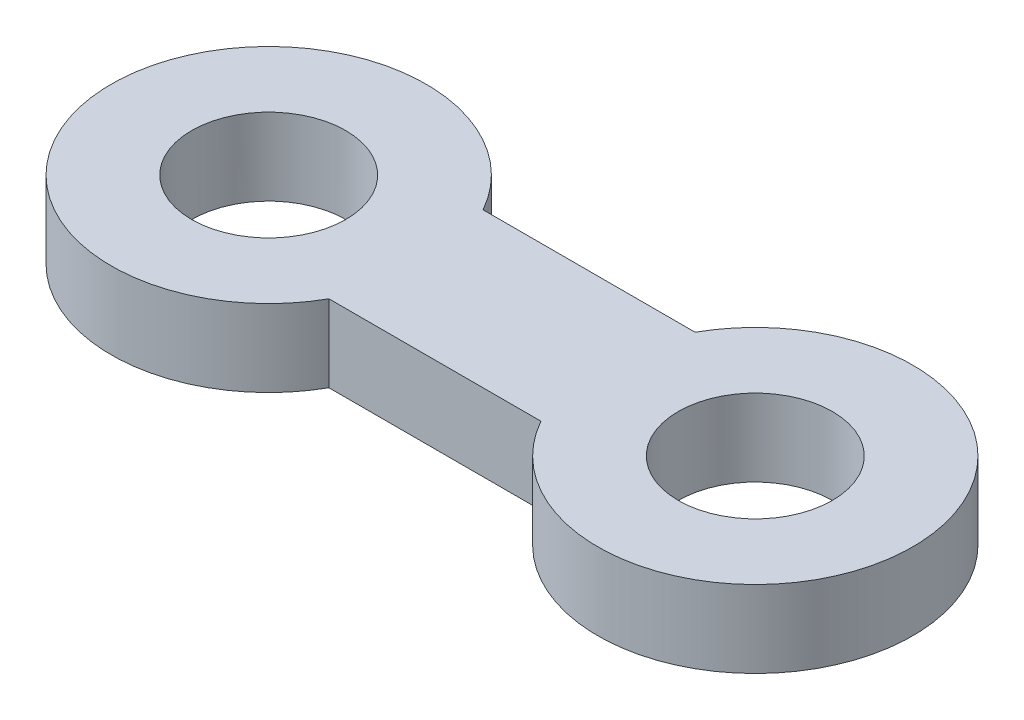
SolidWorks part; units mm, degrees
ref_plane "Front Plane" through (0, 0, 0) normal (0, 0, 1) x (1, 0, 0)
ref_plane "Top Plane" through (0, 0, 0) normal (0, 1, 0) x (1, 0, 0)
ref_plane "Right Plane" through (0, 0, 0) normal (1, 0, 0) x (0, 0, -1)
sketch "Sketch4" plane through (0, 0, 0) normal (0, 1, 0) x (1, 0, 0)
  line L0 (0, 0) -> (0, -116.8928) construction
  line L1 (-27.5, 20) -> (27.5, 20)
  line L2 (-27.5, 20) -> (-27.5, -20)
  line L3 (-27.5, -20) -> (27.5, -20)
  line L4 (27.5, 20) -> (27.5, -20)
  line L5 (-27.5, 20) -> (27.5, -20) construction
  line L6 (-27.5, -20) -> (27.5, 20) construction
  circle A1 centre (-63.1342, 0) radius 40.8631
  circle A2 centre (63.1342, 0) radius 40.8631
  point P0 (0, 0)
  dimension "D1" = 40
  dimension "D2" = 55
extrude "Boss-Extrude1" add sketch "Sketch4" along normal blind 20 contours L3 A2 L1 A1 | A2 L4 | A2 L4
sketch "Sketch6" plane through (0, 0, 0) normal (0, -1, 0) x (1, 0, 0)
  circle A0 centre (-63.1342, 0) radius 20
  circle A1 centre (63.1342, 0) radius 20
  dimension "D1" = 40
extrude "Cut-Extrude1" cut sketch "Sketch6" against normal up to next contours A1 | A0
